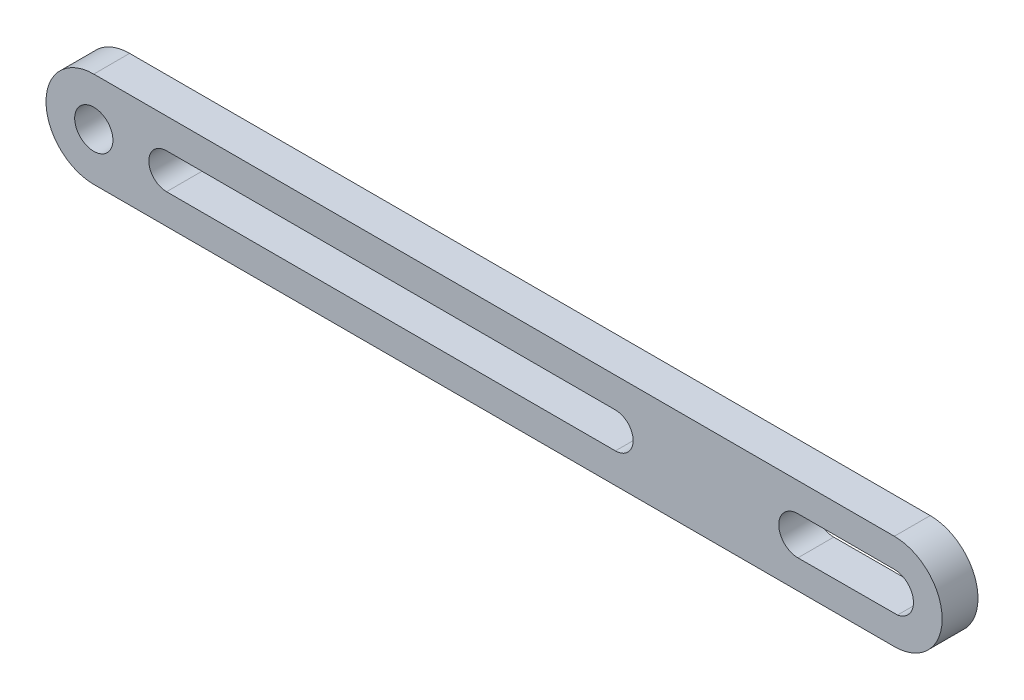
SolidWorks part; units mm, degrees
ref_plane "前视基准面" through (0, 0, 0) normal (0, 0, 1) x (1, 0, 0)
ref_plane "上视基准面" through (0, 0, 0) normal (0, 1, 0) x (1, 0, 0)
ref_plane "右视基准面" through (0, 0, 0) normal (1, 0, 0) x (0, 0, -1)
sketch "草图1" plane through (0, 0, 0) normal (0, 0, 1) x (1, 0, 0)
  line L0 (-53.8502, 4) -> (13.1498, 4)
  line L1 (-53.8502, -4) -> (13.1498, -4)
  line L2 (-47.7619, 0) -> (-10.1946, 0) construction
  line L3 (-47.7619, 1.4835) -> (-10.1946, 1.4835)
  line L4 (-47.7619, -1.4835) -> (-10.1946, -1.4835)
  line L5 (5.0765, 1.6) -> (13.1498, 1.6)
  line L6 (5.0765, -1.6) -> (13.1498, -1.6)
  line L7 (-47.7619, 1.4835) -> (-10.1946, 1.4835)
  circle A3 centre (5.0765, 0) radius 1.6 construction
  arc A4 (-53.8502, 4) -> (-53.8502, -4) centre (-53.8502, 0) ccw
  circle A5 centre (-53.8502, 0) radius 1.6
  arc A9 (-47.7619, 1.4835) -> (-47.7619, -1.4835) centre (-47.7619, 0) ccw
  arc A10 (-10.1946, -1.4835) -> (-10.1946, 1.4835) centre (-10.1946, 0) ccw
  circle A12 centre (13.1498, 0) radius 4 construction
  circle A13 centre (13.1498, 0) radius 1.6 construction
  arc A14 (13.1498, 4) -> (13.1498, -4) centre (13.1498, 0) cw
  arc A15 (13.1498, 1.6) -> (13.1498, -1.6) centre (13.1498, 0) cw
  arc A16 (5.0765, 1.6) -> (5.0765, -1.6) centre (5.0765, 0) ccw
  point P15 (-28.9782, 0)
  point P22 (0, 0)
  dimension "D1" = 67
  dimension "D2" = 67
  dimension "D7" = 8
  dimension "D8" = 3.2
extrude "凸台-拉伸1" add sketch "草图1" along normal blind 3 contours L1 A14 L0 A4
sketch "草图7" plane through (0, 0, 3) normal (0, 0, 1) x (1, 0, 0)
  line L0 (-47.7619, 1.4835) -> (-10.1946, 1.4835)
  line L1 (-47.7619, -1.4835) -> (-10.1946, -1.4835)
  line L2 (5.0765, 1.6) -> (13.1498, 1.6)
  line L3 (5.0765, -1.6) -> (13.4124, -1.5783)
  circle A0 centre (-53.8502, 0) radius 1.6
  arc A1 (-47.7619, 1.4835) -> (-47.7619, -1.4835) centre (-47.7619, 0) ccw
  arc A2 (-10.1946, 1.4835) -> (-10.1946, -1.4835) centre (-10.1946, 0) cw
  arc A3 (13.1498, 1.6) -> (13.4124, -1.5783) centre (13.1498, 0) cw
  arc A4 (5.0765, 1.6) -> (5.0765, -1.6) centre (5.0765, 0) ccw
extrude "切除-拉伸1" cut sketch "草图7" against normal blind 3
